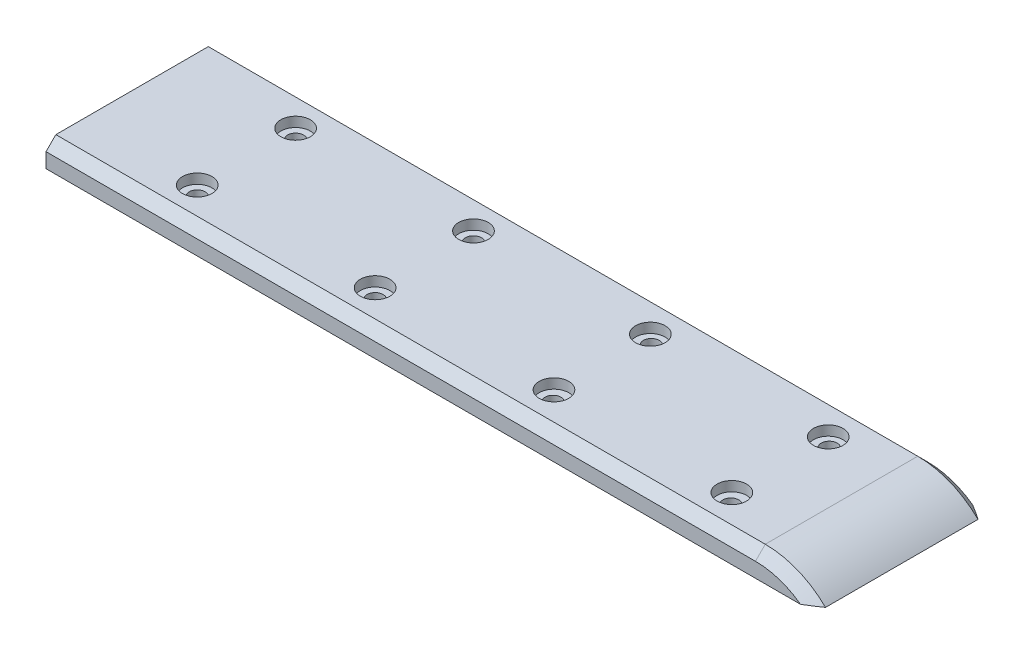
SolidWorks part; units mm, degrees
ref_plane "Front Plane" through (0, 0, 0) normal (0, 0, 1) x (1, 0, 0)
ref_plane "Top Plane" through (0, 0, 0) normal (0, 1, 0) x (1, 0, 0)
ref_plane "Right Plane" through (0, 0, 0) normal (1, 0, 0) x (0, 0, -1)
sketch "Sketch1" plane through (0, 0, 0) normal (0, 0, 1) x (1, 0, 0)
  line L0 (-75, 0) -> (75, 0) construction
  line L4 (-75, 17.5) -> (75, 17.5)
  line L6 (87.2474, 12.5) -> (-87.2474, 12.5)
  arc A2 (-75, 17.5) -> (-87.2474, 12.5) centre (-75, 0) ccw
  arc A3 (87.2474, 12.5) -> (75, 17.5) centre (75, 0) ccw
  point P2 (0, 0)
  point P5 (0, 0)
  dimension "D1" = 17.5
  dimension "D2" = 150
  dimension "D3" = 5
extrude "Boss-Extrude1" add sketch "Sketch1" along normal mid plane 35
sketch "Sketch2" plane through (0, 0, 0) normal (0, 0, 1) x (1, 0, 0)
  line L0 (75, 17.5) -> (-75, 17.5) construction
  line L1 (-87.2474, 12.5) -> (-69.2474, 12.5)
  line L2 (-87.2474, 12.5) -> (-87.2474, 17.5)
  line L3 (-87.2474, 17.5) -> (-69.2474, 17.5)
  line L4 (-69.2474, 12.5) -> (-69.2474, 17.5)
  dimension "D1" = 18
extrude "Cut-Extrude1" cut sketch "Sketch2" against normal mid plane 35
sketch "Sketch3" plane through (0, 12.5, 0) normal (0, -1, 0) x (1, 0, 0)
  line L0 (-69.2474, -17.5) -> (-69.2474, 17.5) construction
  line L1 (-69.2474, -17.5) -> (87.2474, -17.5) construction
  circle A0 centre (-46, -10) radius 1.625
  circle A1 centre (-9.8333, -10) radius 1.625
  circle A2 centre (26.3333, -10) radius 1.625
  circle A3 centre (62.5, -10) radius 1.625
  dimension "D1" = 3.25
  dimension "D2" = 36.1667
  dimension "D3" = 36.1667
  dimension "D4" = 36.1667
  dimension "D5" = 23.2474
  dimension "D6" = 7.5
extrude "Cut-Extrude2" cut sketch "Sketch3" against normal up to surface (5 mm away) up to face at (2.8763, 17.5, 0)
sketch "Sketch4" plane through (0, 17.5, 0) normal (0, 1, 0) x (1, 0, 0)
  circle A0 centre (62.5, 9.8) radius 3
  circle A1 centre (26.3333, 9.8) radius 3
  circle A2 centre (-9.8333, 10) radius 3
  circle A3 centre (-46, 10) radius 3
  dimension "D1" = 6
extrude "Cut-Extrude3" cut sketch "Sketch4" against normal blind 2
mirror "Mirror1" about plane through (0, 0, 0) normal (0, 0, 1) of "Cut-Extrude3", "Cut-Extrude2"
chamfer "Chamfer1" distance 2 angle 45 4 edges at (81.6144, 16.2019, 17.5) (2.8763, 17.5, 17.5) (81.6144, 16.2019, -17.5) (2.8763, 17.5, -17.5)
